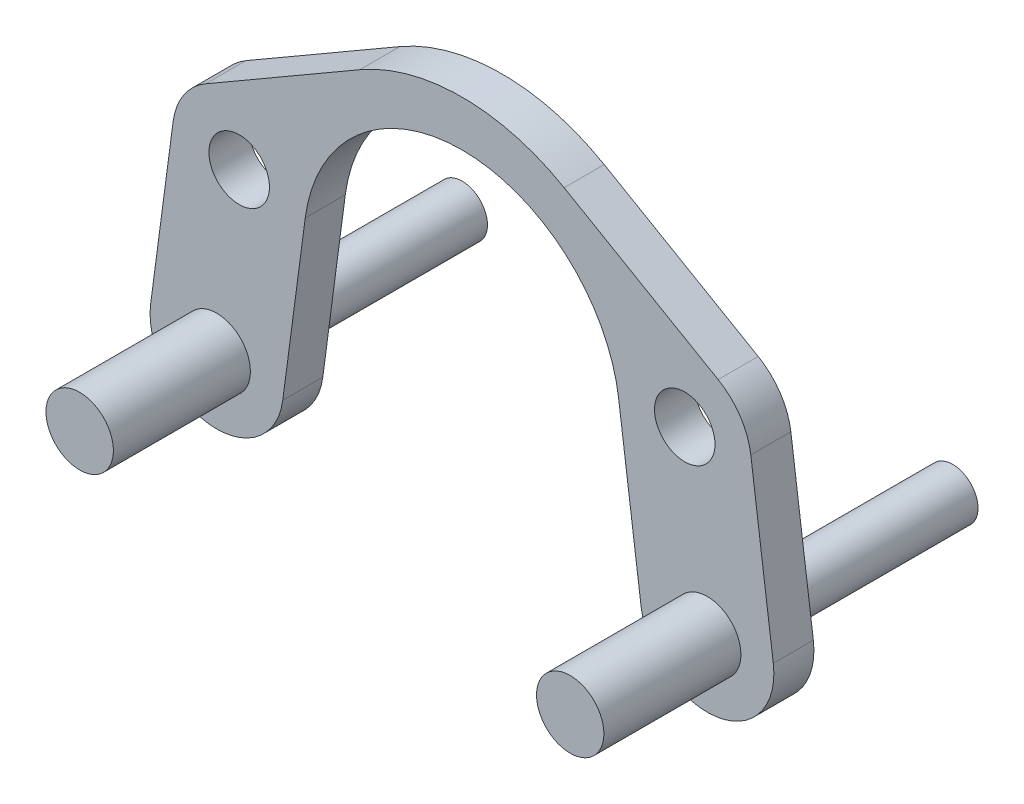
SolidWorks part; units mm, degrees
ref_plane "Front Plane" through (0, 0, 0) normal (0, 0, 1) x (1, 0, 0)
ref_plane "Top Plane" through (0, 0, 0) normal (0, 1, 0) x (1, 0, 0)
ref_plane "Right Plane" through (0, 0, 0) normal (1, 0, 0) x (0, 0, -1)
sketch "Sketch1" plane through (0, 0, 0) normal (0, 0, 1) x (1, 0, 0)
  line L0 (-38.1, 0) -> (38.1, 0) construction
  line L1 (38.1, 0) -> (34.6075, 26.289) construction
  line L2 (0, 0) -> (0, 46.2524) construction
  line L3 (27.8396, -1.3631) -> (24.3471, 24.9259)
  line L4 (48.3604, 1.3631) -> (44.8679, 27.6521)
  line L5 (15.8734, 49.0998) -> (39.7948, 35.2458)
  line L7 (-38.1, 0) -> (-34.6075, 26.289) construction
  line L8 (-15.8734, 49.0998) -> (-39.7948, 35.2458)
  line L9 (-48.3604, 1.3631) -> (-44.8679, 27.6521)
  line L10 (-27.8396, -1.3631) -> (-24.3471, 24.9259)
  arc A1 (27.8396, -1.3631) -> (48.3604, 1.3631) centre (38.1, 0) ccw
  circle A2 centre (34.6075, 26.289) radius 4.699
  arc A3 (44.8679, 27.6521) -> (39.7948, 35.2458) centre (34.6075, 26.289) ccw
  arc A4 (24.3471, 24.9259) -> (0, 46.2524) centre (0, 21.6914) ccw
  arc A6 (15.8734, 49.0998) -> (-15.8734, 49.0998) centre (0, 21.6914) ccw
  arc A7 (31.3972, 25.8625) -> (0, 53.3644) centre (0, 21.6914) ccw construction
  arc A8 (-24.3471, 24.9259) -> (0, 46.2524) centre (0, 21.6914) cw
  arc A9 (-44.8679, 27.6521) -> (-39.7948, 35.2458) centre (-34.6075, 26.289) cw
  circle A10 centre (-34.6075, 26.289) radius 4.699
  arc A11 (-27.8396, -1.3631) -> (-48.3604, 1.3631) centre (-38.1, 0) cw
  point P20 (0, 0)
  dimension "D2" = 20.701
  dimension "D5" = 9.398
  dimension "D1" = 38.1
  dimension "D3" = 34.6075
  dimension "D4" = 26.289
  dimension "D6" = 7.112
  dimension "D7" = 10.3505
extrude "Boss-Extrude1" add sketch "Sketch1" along normal blind 6.223
sketch "Sketch2" plane through (0, 0, 6.223) normal (0, 0, 1) x (1, 0, 0)
  circle A0 centre (38.1, 0) radius 5.2324
  arc A1 (27.8396, -1.3631) -> (48.3604, 1.3631) centre (38.1, 0) ccw construction
  dimension "D1" = 10.4648
extrude "Boss-Extrude2" add sketch "Sketch2" along normal blind 21.2852
mirror "Mirror1" about plane through (0, 0, 0) normal (1, 0, 0) of "Boss-Extrude2"
sketch "Sketch3" plane through (0, 0, 0) normal (0, 0, -1) x (-1, 0, 0)
  circle A0 centre (38.1, 0) radius 3.937
  arc A1 (27.8396, -1.3631) -> (48.3604, 1.3631) centre (38.1, 0) ccw construction
  dimension "D1" = 7.874
extrude "Boss-Extrude3" add sketch "Sketch3" along normal blind 31.9024
mirror "Mirror2" about plane through (0, 0, 0) normal (1, 0, 0) of "Boss-Extrude3"
